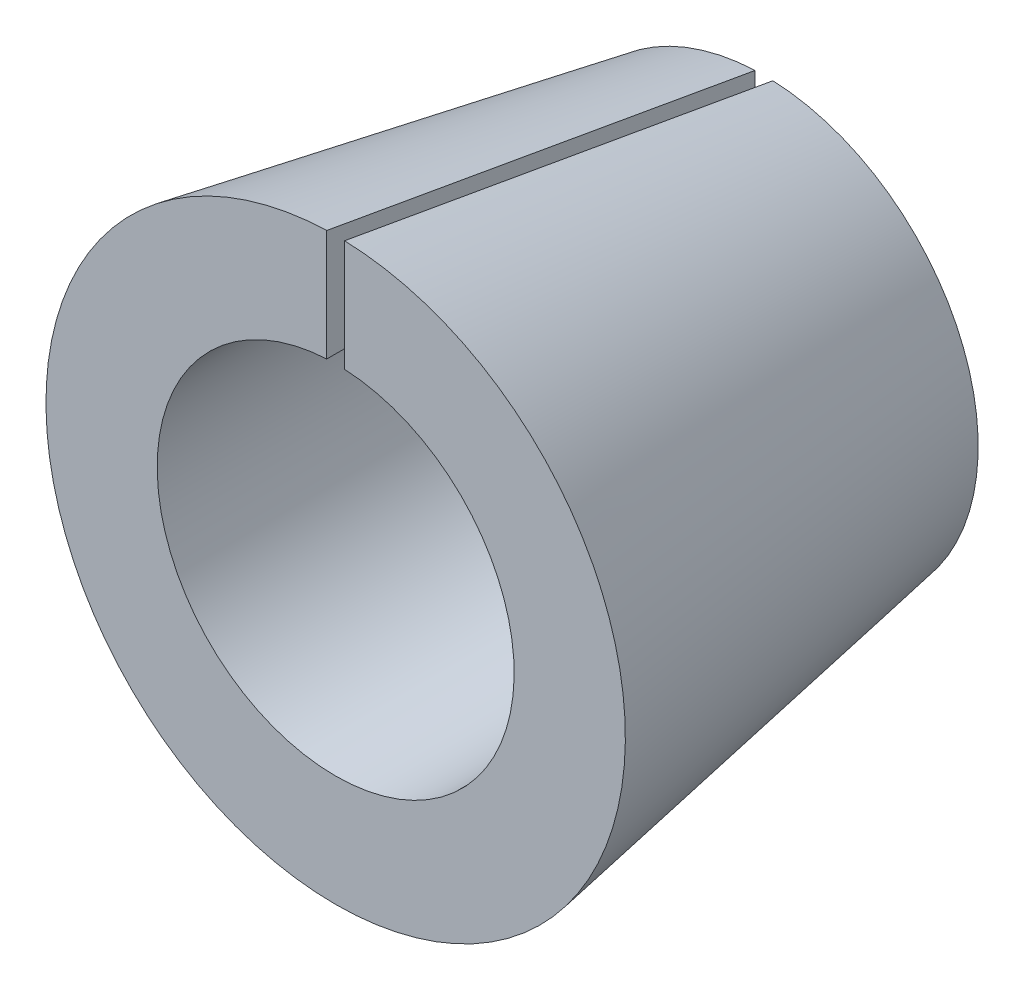
SolidWorks part; units mm, degrees
material "Alloy Steel"
ref_plane "Front Plane" through (0, 0, 0) normal (0, 0, 1) x (1, 0, 0)
ref_plane "Top Plane" through (0, 0, 0) normal (0, 1, 0) x (1, 0, 0)
ref_plane "Right Plane" through (0, 0, 0) normal (1, 0, 0) x (0, 0, -1)
sketch "Sketch1" plane through (0, 0, 0) normal (1, 0, 0) x (0, 0, -1)
  line L1 (0, 8.1159) -> (0, 5)
  line L2 (12, 5) -> (12, 6)
  line L3 (12, 6) -> (0, 8.1159)
  line L4 (12, 5) -> (0, 5)
  line L5 (14.1891, 0) -> (-5.3368, 0) construction
  dimension "D1" = 12
  dimension "D2" = 10
  dimension "D3" = 10
  dimension "D4" = 12
revolve "Revolve1" add sketch "Sketch1" angle 360 about L5
sketch "Sketch2" plane through (0, 0, 0) normal (0, 0, 1) x (1, 0, 0)
  line L1 (-0.25, 8.1159) -> (0.25, 8.1159)
  line L2 (-0.25, 8.1159) -> (-0.25, 0)
  line L3 (-0.25, 0) -> (0.25, 0)
  line L4 (0.25, 8.1159) -> (0.25, 0)
  circle A0 centre (0, 0) radius 8.1159 construction
  dimension "D1" = 0.5
extrude "Cut-Extrude1" cut sketch "Sketch2" against normal up to next
